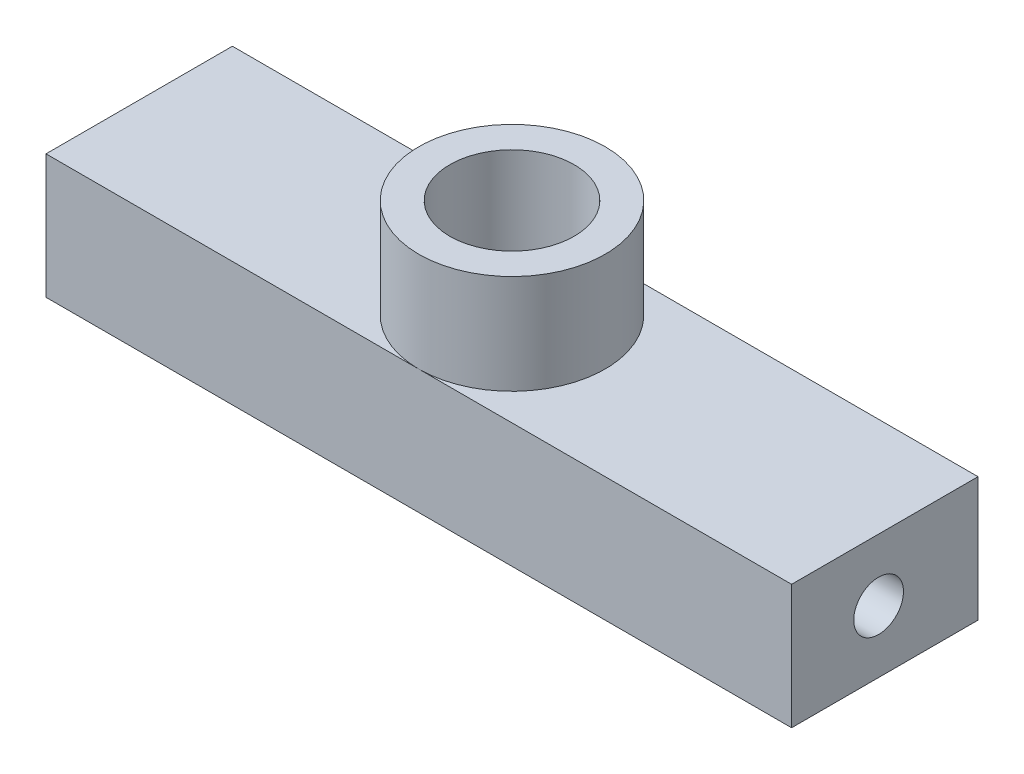
SolidWorks part; units mm, degrees
ref_plane "Front Plane" through (0, 0, 0) normal (0, 0, 1) x (1, 0, 0)
ref_plane "Top Plane" through (0, 0, 0) normal (0, 1, 0) x (1, 0, 0)
ref_plane "Right Plane" through (0, 0, 0) normal (1, 0, 0) x (0, 0, -1)
sketch "Sketch1" plane through (0, 0, 0) normal (0, 1, 0) x (1, 0, 0)
  line L1 (-15, 3.75) -> (15, 3.75)
  line L2 (-15, 3.75) -> (-15, -3.75)
  line L3 (-15, -3.75) -> (15, -3.75)
  line L4 (15, 3.75) -> (15, -3.75)
  line L5 (-15, 3.75) -> (15, -3.75) construction
  line L6 (-15, -3.75) -> (15, 3.75) construction
  point P0 (0, 0)
  dimension "D1" = 30
  dimension "D2" = 7.5
extrude "Boss-Extrude1" add sketch "Sketch1" along normal blind 5
sketch "Sketch2" plane through (0, 5, 0) normal (0, 1, 0) x (1, 0, 0)
  circle A0 centre (0, 0) radius 3.75
  circle A1 centre (0, 0) radius 2.5
  dimension "D1" = 7.5
  dimension "D2" = 5
extrude "Boss-Extrude2" add sketch "Sketch2" along normal blind 4
sketch "Sketch3" plane through (0, 0, 0) normal (0, -1, 0) x (1, 0, 0)
  circle A0 centre (0, 0) radius 1.75
  dimension "D1" = 3.5
extrude "Cut-Extrude1" cut sketch "Sketch3" against normal through all
sketch "Sketch4" plane through (0, 0, 0) normal (0, -1, 0) x (-1, 0, 0)
  circle A0 centre (0, 0) radius 2.5
  dimension "D1" = 5
extrude "Cut-Extrude3" cut sketch "Sketch4" against normal blind 4
sketch "Sketch5" plane through (15, 0, 0) normal (1, 0, 0) x (0, 0, -1)
  line L0 (3.75, 5) -> (3.75, 0) construction
  line L1 (-3.75, 5) -> (3.75, 5) construction
  circle A0 centre (-0.25, 2.5) radius 1
  dimension "D1" = 2
  dimension "D2" = 4
  dimension "D3" = 2.5
extrude "Cut-Extrude4" cut sketch "Sketch5" against normal blind 10
sketch "Sketch6" plane through (-15, 0, 0) normal (-1, 0, 0) x (0, 0, 1)
  line L0 (-3.75, 5) -> (-3.75, 0) construction
  line L1 (-3.75, 5) -> (3.75, 5) construction
  circle A0 centre (0.25, 2.5) radius 1
  dimension "D1" = 2
  dimension "D2" = 4
  dimension "D3" = 2.5
extrude "Cut-Extrude5" cut sketch "Sketch6" against normal blind 10
